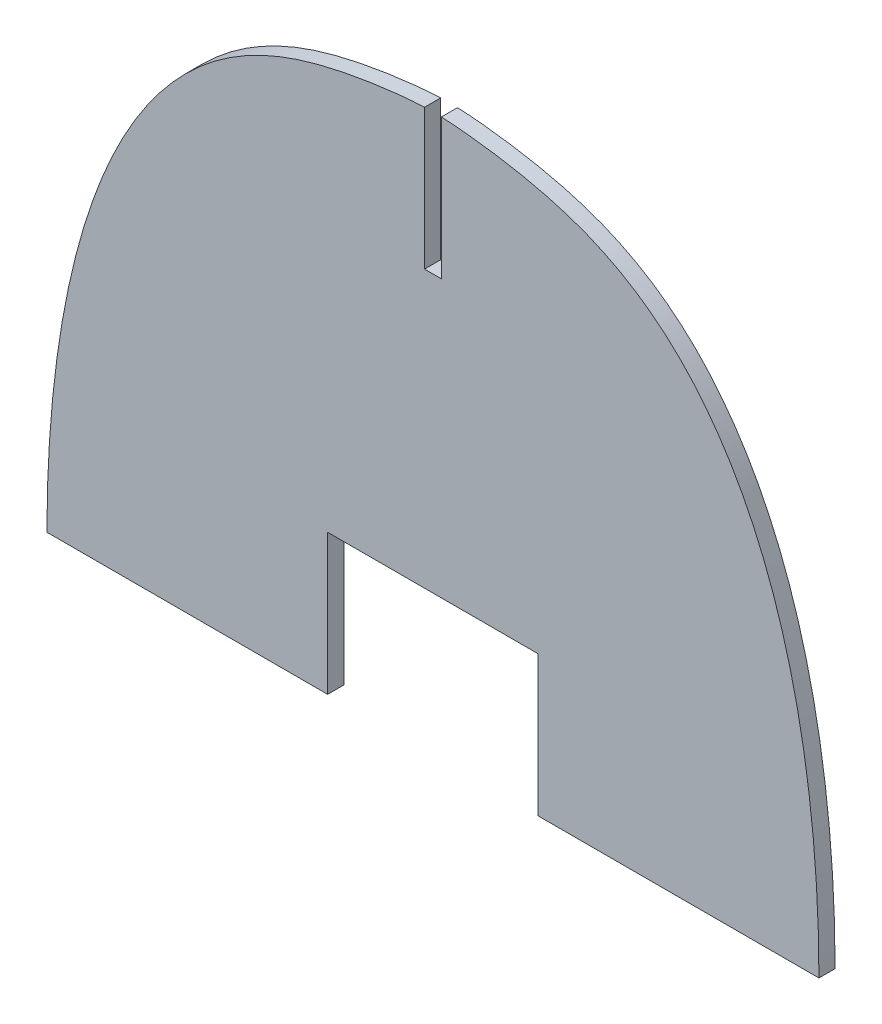
SolidWorks part; units mm, degrees
ref_plane "Front" through (0, 0, 0) normal (0, 0, 1) x (1, 0, 0)
ref_plane "Top" through (0, 0, 0) normal (0, 1, 0) x (1, 0, 0)
ref_plane "Right" through (0, 0, 0) normal (1, 0, 0) x (0, 0, -1)
sketch "Sketch1" plane through (0, 0, 0) normal (0, 0, 1) x (1, 0, 0)
  line L1 (0, 241.3) -> (96.9709, 241.3) construction
  line L2 (139.7, 39.6875) -> (139.7, 103.1967) construction
  spline S0 degree 3 poles (0, 241.3) (9.0082, 241.3) (56.6569, 236.3591) (128.7829, 181.9054) (139.7, 89.9228) (139.7, 39.6875) knots 0 0 0 0 0.176272 0.390302 1 1 1 1
sketch "Sketch2" plane through (0, 0, 0) normal (0, 0, 1) x (1, 0, 0)
  line L0 (139.7, 39.6875) -> (0, 39.6875)
  line L1 (0, 39.6875) -> (0, 241.3)
  spline S0 degree 3 poles (3999.0522, 224.9444) (-360.212, 160.6417) (-15.0452, 290.4928) (318.6517, 38.5584) (-285.8062, -979.3067) (1175.8528, 3901.8027) knots -0.994122 -0.994122 -0.994122 -0.994122 0.176272 0.390302 3.632457 3.632457 3.632457 3.632457 only from (0, 241.3) to (139.7, 39.6875) construction
  spline S1 degree 3 poles (0, 241.3) (9.0082, 241.3) (56.6569, 236.3591) (128.7829, 181.9054) (139.7, 89.9228) (139.7, 39.6875) knots 0 0 0 0 0.176272 0.390302 1 1 1 1
extrude "Boss-Extrude1" add sketch "Sketch2" along normal blind 5.842
sketch "Sketch3" plane through (0, 0, 5.842) normal (0, 0, 1) x (1, 0, 0)
  line L1 (0, 39.6875) -> (38.1, 39.6875)
  line L2 (0, 39.6875) -> (0, 90.4875)
  line L3 (0, 90.4875) -> (38.1, 90.4875)
  line L4 (38.1, 39.6875) -> (38.1, 90.4875)
  line L5 (0, 241.3) -> (3.048, 241.3)
  line L6 (0, 241.3) -> (0, 190.5)
  line L7 (0, 190.5) -> (3.048, 190.5)
  line L8 (3.048, 241.3) -> (3.048, 190.5)
  dimension "D1" = 38.1
  dimension "D2" = 50.8
  dimension "D3" = 50.8
  dimension "D4" = 3.048
extrude "Cut-Extrude1" cut sketch "Sketch3" against normal through all
mirror "Mirror1" about plane through (0, 0, 0) normal (1, 0, 0) of bodies 102
